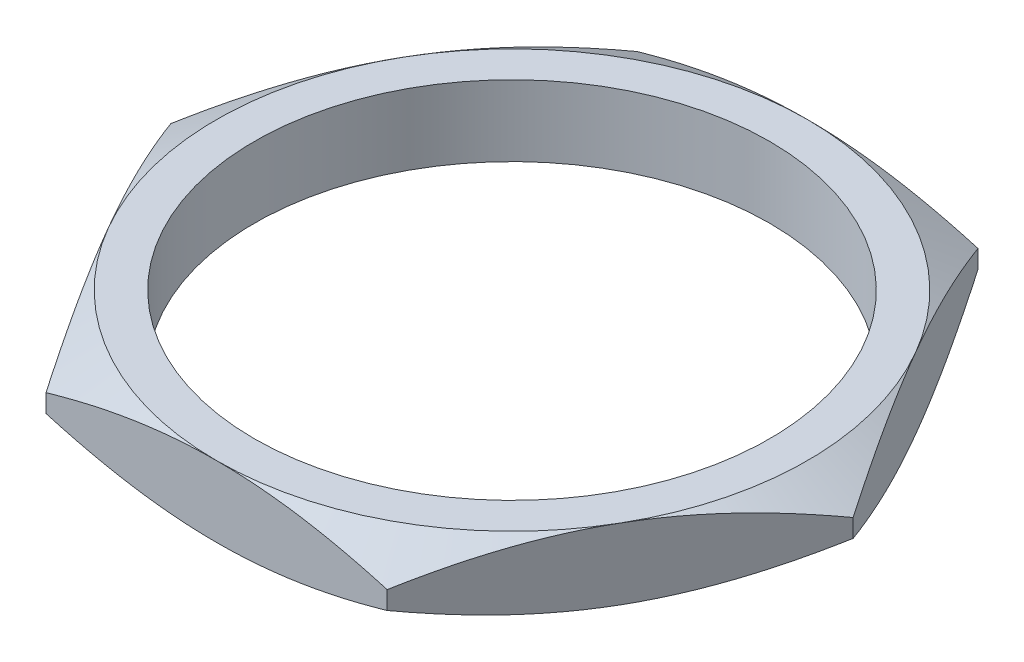
SolidWorks part; units mm, degrees
ref_plane "Front Plane" through (0, 0, 0) normal (0, 0, 1) x (1, 0, 0)
ref_plane "Top Plane" through (0, 0, 0) normal (0, 1, 0) x (1, 0, 0)
ref_plane "Right Plane" through (0, 0, 0) normal (1, 0, 0) x (0, 0, -1)
sketch "Sketch1" plane through (0, 0, 0) normal (0, 1, 0) x (1, 0, 0)
  line L1 (14.4338, 0) -> (7.2169, 12.5)
  line L2 (7.2169, 12.5) -> (-7.2169, 12.5)
  line L3 (-7.2169, 12.5) -> (-14.4338, 0)
  line L4 (-14.4338, 0) -> (-7.2169, -12.5)
  line L5 (-7.2169, -12.5) -> (7.2169, -12.5)
  line L6 (7.2169, -12.5) -> (14.4338, 0)
  circle A0 centre (0, 0) radius 10.9
  circle A1 centre (0, 0) radius 12.5 construction
  dimension "D1" = 21.8
  dimension "D2" = 25
extrude "Boss-Extrude1" add sketch "Sketch1" along normal blind 3 contours L3 L4 L5 L6 L1 L2
ref_plane "Plane1" through (0, 1.5, 0) normal (0, 1, 0) x (1, 0, 0)
sketch "Sketch2" plane through (0, 3, 0) normal (0, 1, 0) x (1, 0, 0)
  line L0 (-7.2169, 12.5) -> (-14.4338, 0) construction
  circle A0 centre (0, 0) radius 12.5
extrude "Cut-Extrude1" cut sketch "Sketch2" against normal through all draft 60 flip side to cut
mirror "Mirror1" about plane through (0, 1.5, 0) normal (0, 1, 0) of "Cut-Extrude1"
